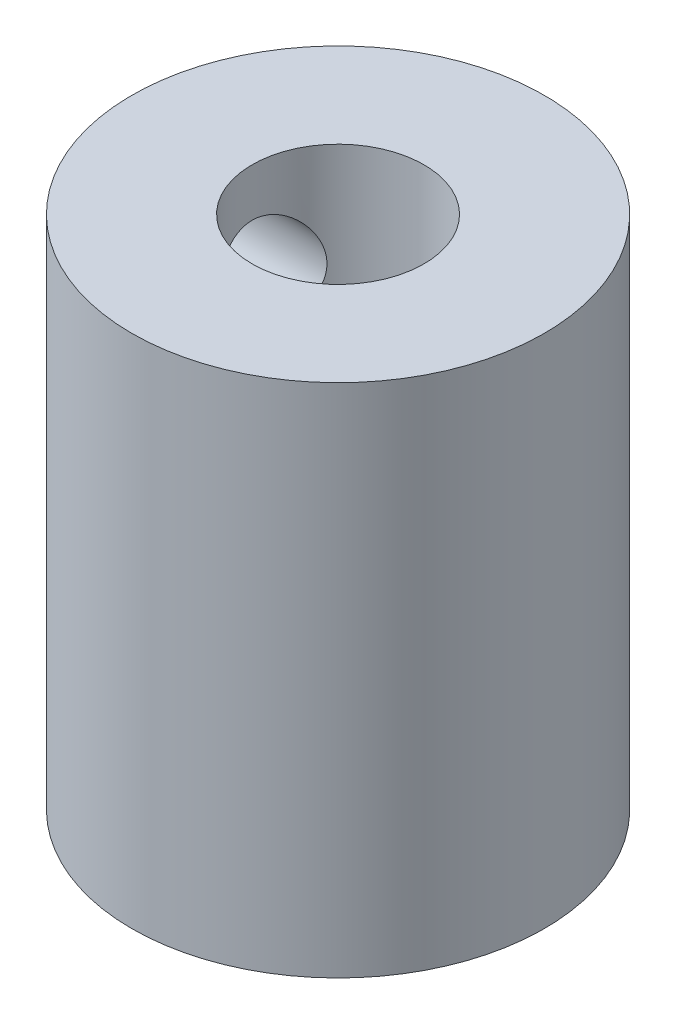
SolidWorks part; units mm, degrees
ref_plane "Front Plane" through (0, 0, 0) normal (0, 0, 1) x (1, 0, 0)
ref_plane "Top Plane" through (0, 0, 0) normal (0, 1, 0) x (1, 0, 0)
ref_plane "Right Plane" through (0, 0, 0) normal (1, 0, 0) x (0, 0, -1)
sketch "Sketch1" plane through (0, 0, 0) normal (0, 1, 0) x (1, 0, 0)
  circle A0 centre (0, 0) radius 3.175
  circle A1 centre (0, 0) radius 7.62
extrude "Boss-Extrude1" add sketch "Sketch1" along normal blind 19.05
sketch "Sketch2" plane through (0, 0, 0) normal (1, 0, 0) x (0, 0, -1)
  line L2 (-7.62, 0) -> (7.62, 0) construction
  line L3 (7.62, 19.05) -> (-7.62, 19.05) construction
  circle A0 centre (0, 3.81) radius 2.032
  circle A1 centre (0, 15.24) radius 2.032
  dimension "D1" = 3.81
  dimension "D2" = 3.81
extrude "Cut-Extrude1" cut sketch "Sketch2" against normal through all
